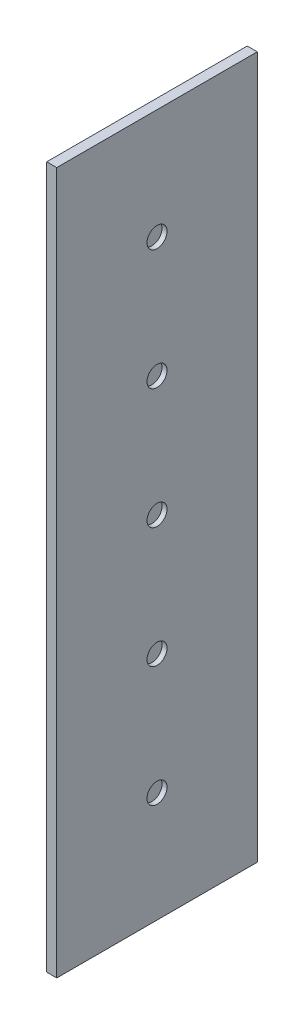
SolidWorks part; units mm, degrees
ref_plane "Alzado" through (0, 0, 0) normal (0, 0, 1) x (1, 0, 0)
ref_plane "Planta" through (0, 0, 0) normal (0, 1, 0) x (1, 0, 0)
ref_plane "Vista lateral" through (0, 0, 0) normal (1, 0, 0) x (0, 0, -1)
sketch "Croquis1" plane through (0, 0, 0) normal (0, 0, 1) x (1, 0, 0)
  line L1 (0, 0) -> (10, 0)
  line L2 (0, 0) -> (0, 700)
  line L3 (0, 700) -> (10, 700)
  line L4 (10, 0) -> (10, 700)
  dimension "D1" = 10
  dimension "D2" = 700
extrude "Saliente-Extruir1" add sketch "Croquis1" along normal blind 200
sketch "Croquis2" plane through (10, 0, 0) normal (1, 0, 0) x (0, 0, -1)
  circle A0 centre (-100, 110) radius 10
  circle A1 centre (-100, 230) radius 10
  circle A2 centre (-100, 350) radius 10
  circle A3 centre (-100, 470) radius 10
  circle A4 centre (-100, 590) radius 10
extrude "Cortar-Extruir1" cut sketch "Croquis2" against normal blind 5
